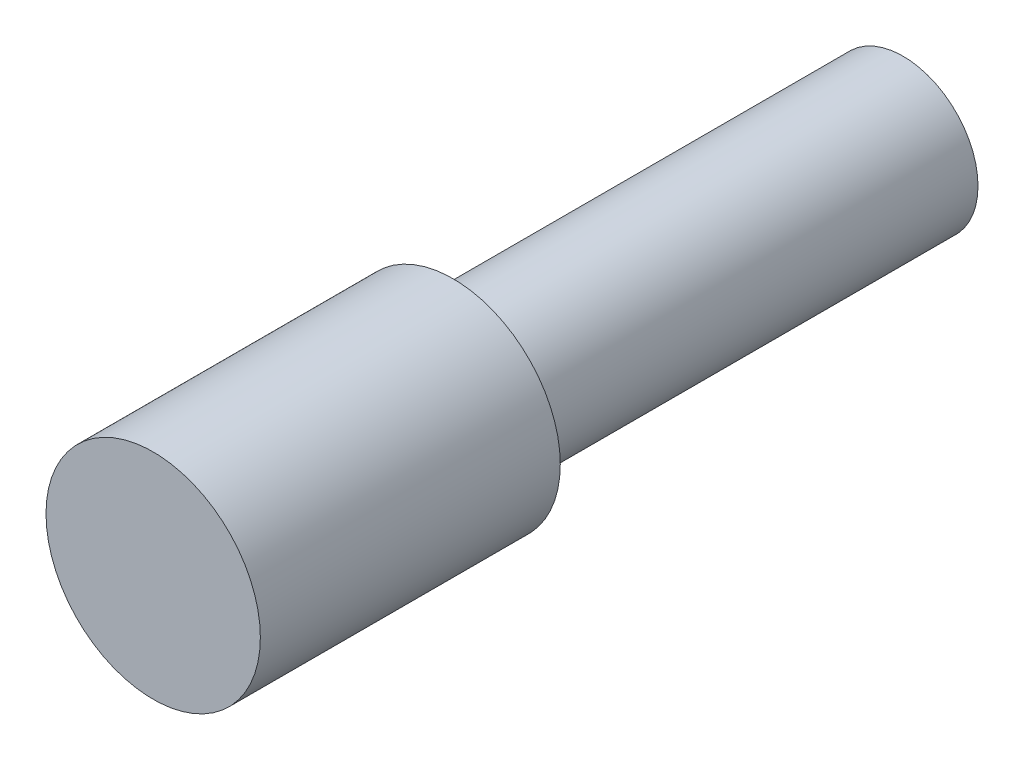
SolidWorks part; units mm, degrees
ref_plane "Спереди" through (0, 0, 0) normal (0, 0, 1) x (1, 0, 0)
ref_plane "Сверху" through (0, 0, 0) normal (0, 1, 0) x (1, 0, 0)
ref_plane "Справа" through (0, 0, 0) normal (1, 0, 0) x (0, 0, -1)
sketch "Эскиз2" plane through (0, 0, 0) normal (0, 0, 1) x (1, 0, 0)
  circle A0 centre (0, 0) radius 5
  dimension "D1" = 10
extrude "Бобышка-Вытянуть1" add sketch "Эскиз2" along normal blind 50
thread "Резьба1" pitch 1 start angle 0, offset 0, length 10, pitch 1, diameter 10
ref_plane "Плоскость5" through (-5, 0, 50) normal (0, -1, 0) x (-1, 0, 0)
sketch "Профиль резьбы2" plane through (-5, 0, 50) normal (0, -1, 0) x (-1, 0, 0)
  line L0 (0, 0) -> (0, 1) construction
  line L11 (0, 0) -> (0, 0.875)
  line L12 (0, 0.875) -> (-0.5413, 0.5625)
  line L13 (-0.5413, 0.5625) -> (-0.5413, 0.3125)
  line L15 (-0.5413, 0.3125) -> (0, 0)
  line L17 (-0.5413, 0.4375) -> (0, 0.4375) construction
  point P2 (0, 0)
  dimension "Pitch" = 1
  dimension "Profile_Angle" = 60
  dimension "Profile_Land" = 0.25
  dimension "Profile_Height" = 0.5413
sketch "Эскиз8" plane through (0, 0, 50) normal (0, 0, 1) x (1, 0, 0)
  circle A0 centre (0, 0) radius 7.1468
extrude "Бобышка-Вытянуть2" add sketch "Эскиз8" against normal blind 20 contours A0
